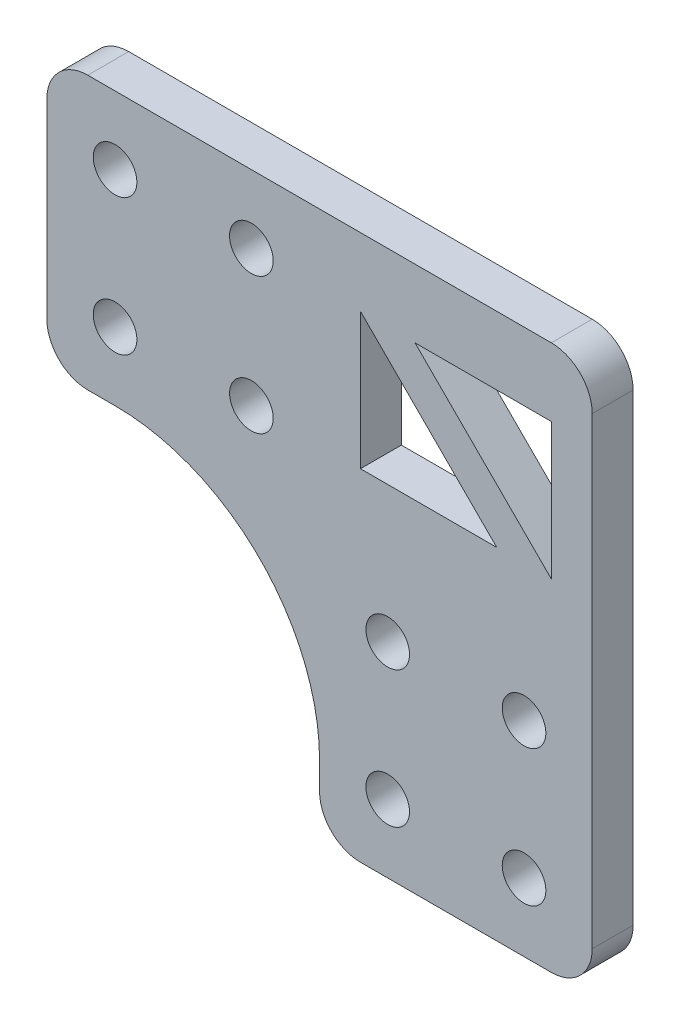
SolidWorks part; units mm, degrees
ref_plane "前视基准面" through (0, 0, 0) normal (0, 0, 1) x (1, 0, 0)
ref_plane "上视基准面" through (0, 0, 0) normal (0, 1, 0) x (1, 0, 0)
ref_plane "右视基准面" through (0, 0, 0) normal (1, 0, 0) x (0, 0, -1)
other "Configuration Table"
sketch "草图1" plane through (0, 0, 0) normal (0, 0, 1) x (1, 0, 0)
  line L0 (0, 0) -> (40, 0)
  line L3 (40, -40) -> (20, -40)
  line L5 (0, -20) -> (0, 0)
  line L6 (30, 0) -> (30, -40) construction
  line L7 (0, -10) -> (30, -10) construction
  line L8 (10, -10) -> (10, 0) construction
  line L9 (30, -30) -> (20.041, -30) construction
  line L10 (23, -5) -> (23, -15)
  line L11 (23, -15) -> (33, -15)
  line L12 (33, -15) -> (23, -5)
  line L13 (27, -5) -> (37, -5)
  line L14 (37, -5) -> (37, -15)
  line L15 (37, -15) -> (27, -5)
  line L19 (0, -20) -> (20, -20)
  line L20 (20, -20) -> (20, -40)
  line L21 (40, 0) -> (40, -40)
  circle A0 centre (5, -5) radius 1.6
  circle A1 centre (15, -5) radius 1.6
  circle A2 centre (15, -15) radius 1.6
  circle A3 centre (5, -15) radius 1.6
  circle A8 centre (25, -35) radius 1.6
  circle A9 centre (35, -35) radius 1.6
  circle A10 centre (35, -25) radius 1.6
  circle A11 centre (25, -25) radius 1.6
  point P3 (0, 0)
  point P23 (0, 0)
  point P24 (40, -40)
  point P25 (30, 0)
  point P26 (27, -5)
  point P27 (0, 0)
  dimension "D8" = 3.2
  dimension "D11" = 3.2
  dimension "D2" = 20
  dimension "D3" = 20
  dimension "D4" = 40
  dimension "D5" = 40
  dimension "D6" = 10
  dimension "D7" = 10
  dimension "D9" = 5
  dimension "D10" = 5
  dimension "D12" = 5
  dimension "D13" = 5
  dimension "D14" = 10
  dimension "D15" = 10
  dimension "D16" = 10
  dimension "D17" = 10
  dimension "D18" = 7
  dimension "D19" = 7
extrude "凸台-拉伸1" add sketch "草图1" along normal blind 3
fillet "圆角1" radius 3 5 edges at (0, 0, 1.5) (20, -40, 1.5) (0, -20, 1.5) (40, -40, 1.5) (40, 0, 1.5)
fillet "圆角2" radius 15 1 edges at (20, -20, 1.5)
